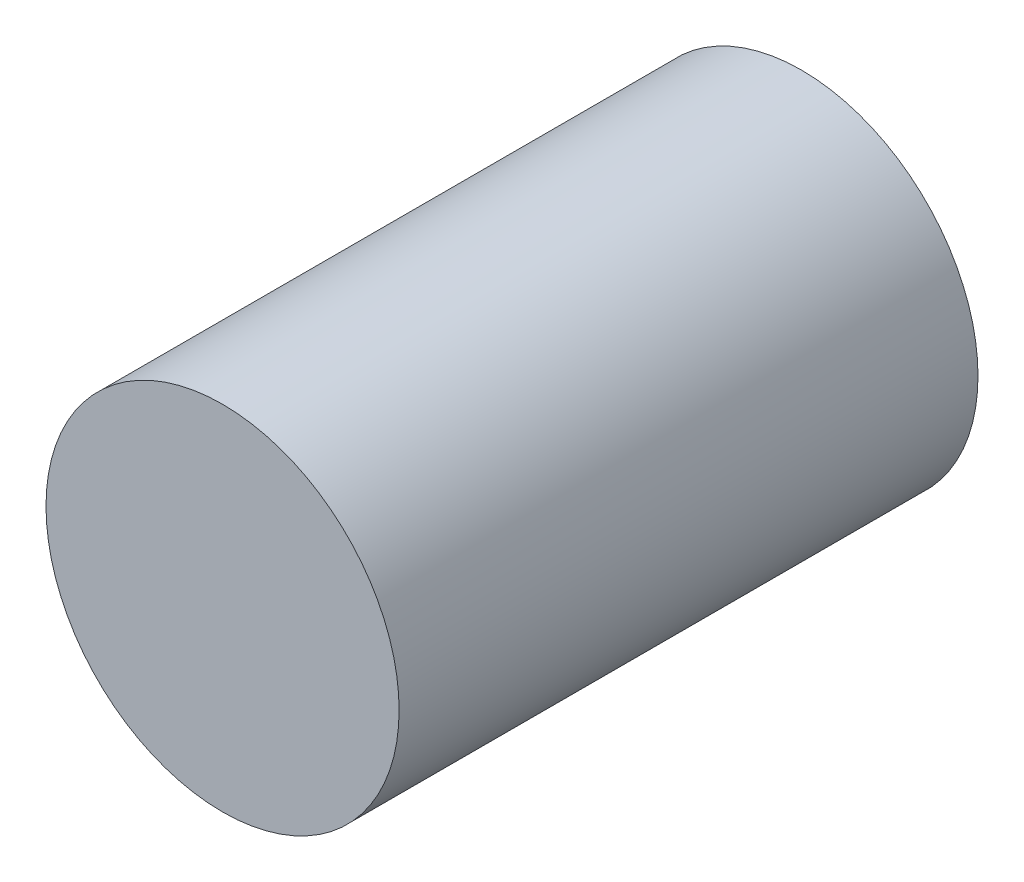
SolidWorks part; units mm, degrees
ref_plane "Front Plane" through (0, 0, 0) normal (0, 0, 1) x (1, 0, 0)
ref_plane "Top Plane" through (0, 0, 0) normal (0, 1, 0) x (1, 0, 0)
ref_plane "Right Plane" through (0, 0, 0) normal (1, 0, 0) x (0, 0, -1)
sketch "Sketch1" plane through (0, 0, 0) normal (0, 0, 1) x (1, 0, 0)
  circle A0 centre (0, 0) radius 61
  dimension "D1" = 122
extrude "Boss-Extrude1" add sketch "Sketch1" along normal mid plane 200
